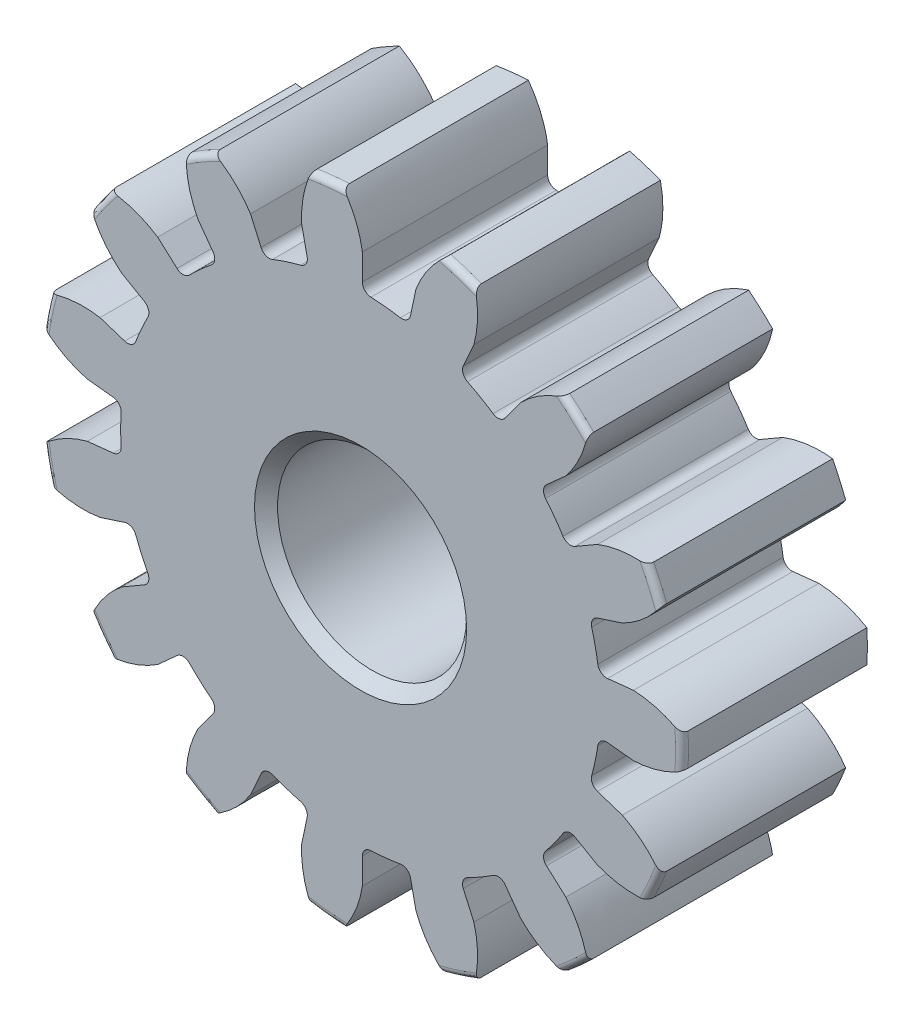
SolidWorks part; units mm, degrees
ref_plane "Front" through (0, 0, 0) normal (0, 0, 1) x (1, 0, 0)
ref_plane "Top" through (0, 0, 0) normal (0, 1, 0) x (1, 0, 0)
ref_plane "Right" through (0, 0, 0) normal (1, 0, 0) x (0, 0, -1)
sketch "Sketch1" plane through (0, 0, 0) normal (0, 0, 1) x (1, 0, 0)
  line L0 (-190.5, 0) -> (190.5, 0) construction
  circle A0 centre (0, 0) radius 10.795
  circle A1 centre (0, 0) radius 9.525 construction
  circle A3 centre (0, 0) radius 8.0556 construction
  dimension "D1" = 1.4694
  dimension "OD" = 21.59
  dimension "Ptich Dia" = 19.05
  dimension "D2" = 2.7394
  dimension "Root Dia" = 16.1112
  dimension "D3" = 1.27
  dimension "Number of Teeth" = 381
extrude "Boss-Extrude1" add sketch "Sketch1" against normal blind 9.525
sketch "Sketch2" plane through (0, 0, 0) normal (1, 0, 0) x (0, 0, -1)
  line L0 (9.525, 0) -> (19.05, 0)
  line L1 (9.525, 0) -> (9.525, 7.7391)
  line L2 (9.525, 7.7391) -> (19.05, 7.7391)
  line L3 (19.05, 7.7391) -> (19.05, 0)
  point P5 (19.05, -7.7391)
  point P6 (0, -10.795)
  point P7 (9.525, -10.795)
  point P9 (0, 10.795)
  dimension "Face Wd" = 9.525
  dimension "B Hub Dia" = 15.4781
  dimension "D O'all Lg." = 19.05
revolve "Revolve1" add sketch "Sketch2" angle 360 mid plane about L0
fillet "Fillet2" radius 0.2159 3 edges at (10.795, 0, -9.525) (10.795, 0, 0) (7.7391, 0, -9.525)
sketch "Sketch3" plane through (0, 0, 0) normal (0, 0, 1) x (1, 0, 0)
  line L0 (0, 0) -> (0, 10.795) construction
  line L1 (-2.3089, 8.9279) -> (0, 9.525)
  line L2 (-9.5921, 9.525) -> (9.5921, 9.525) construction
  line L3 (-9.2865, 7.1233) -> (9.2865, 11.9267) construction
  line L4 (-2.3089, 8.9279) -> (0, 0) construction
  line L5 (-5.7038, 7.246) -> (0, 0) construction
  line L6 (-5.7038, 7.246) -> (-0.8315, 11.0813) construction
  line L7 (-1.61, 9.08) -> (0, 0) construction
  line L8 (-1.61, 9.08) -> (0.0338, 9.3714) construction
  arc A0 (-2.3089, 8.9279) -> (-5.7038, 7.246) centre (0, 0) ccw
  circle A1 centre (0, 0) radius 9.525 construction
  circle A2 centre (0, 0) radius 9.2216 construction
  arc A3 (-2.3089, 8.9279) -> (-1.61, 9.08) centre (0, 0) cw
  circle A4 centre (0, 0) radius 10.795 construction
  point P6 (0, 9.525)
  dimension "D1" = 2.3849
  dimension "Pressure Angle" = 14.5
  dimension "D2" = 3.8158
  dimension "D3" = 6.2007
  dimension "D4" = 0.7155
  dimension "D5" = 1.6694
sketch "Sketch4" plane through (0, 0, 0) normal (0, 0, 1) x (1, 0, 0)
  line L0 (0, 0) -> (0.9902, 9.4209) construction
  line L1 (0.0599, 9.2214) -> (0.0599, 8.0554)
  line L2 (0, 9.525) -> (1.9804, 9.3169) construction
  line L3 (1.8586, 9.0324) -> (1.6162, 7.8918)
  line L4 (0.0599, 8.0554) -> (0, 0) construction
  line L5 (0, 0) -> (0, 10.795) construction
  line L6 (-5.7038, 7.246) -> (-0.8315, 11.0813) construction
  line L7 (-5.7038, 7.246) -> (-0.8315, 11.0813) construction
  arc A0 (1.6162, 7.8918) -> (0.0599, 8.0554) centre (0, 0) ccw
  arc A1 (0, 9.525) -> (1.9804, 9.3169) centre (0, 0) cw construction
  circle A2 centre (0, 0) radius 9.525 construction
  circle A3 centre (0, 0) radius 9.2216 construction
  circle A4 centre (0, 0) radius 8.0556 construction
  arc A5 (3.1173, 10.6663) -> (-0.8315, 11.0813) centre (0, 0) ccw
  spline S0 degree 2 poles (-0.8315, 11.0813) (-0.0963, 10.2474) (0.0599, 9.2214) knots 0 0 0 1 1 1
  spline S1 degree 2 poles (3.1173, 10.6663) (2.2248, 10.0035) (1.8586, 9.0324) knots 0 0 0 1 1 1
  dimension "D1" = 1.9949
extrude "Cut-Extrude1" cut sketch "Sketch4" against normal through all
fillet "Fillet1" radius 0.2992 2 edges at (1.6162, 7.8918, -4.7625) (0.0599, 8.0554, -4.7625)
pattern_circular "CirPattern1" count 15 over 360 about axis through (0, 0, -9.525) along (0, 0, 1) of "Cut-Extrude1", "Fillet1"
sketch "Sketch5" plane through (0, 0, 0) normal (0, 0, 1) x (1, 0, 0)
  circle A0 centre (0, 0) radius 3.175
  circle A1 centre (0, 0) radius 3.175 construction
  dimension "Bore Min" = 6.35
  dimension "Bore Max" = 6.35
extrude "Cut-Extrude2" cut sketch "Sketch5" against normal through all
chamfer "Chamfer1" distance 0.387 angle 45 3 edges at (7.7391, 0, -19.05) (3.175, 0, 0) (3.175, 0, -19.05)
sketch "Pitch Dia" plane through (0, 0, 0) normal (0, 0, 1) x (1, 0, 0)
  circle A0 centre (0, 0) radius 9.525 construction
  circle A1 centre (0, 0) radius 9.525
sketch "Sketch6" plane through (0, 0, -19.05) normal (0, 0, -1) x (-1, 0, 0)
  circle A1 centre (0, 0) radius 12.7
  dimension "D1" = 25.4
extrude "Cut-Extrude3" cut sketch "Sketch6" against normal blind 12.827
equation "\"D1@Boss-Extrude1\" = \"Face Wd@Sketch2\""
equation "\"D2@Sketch3\" = \"D1@Sketch3\"*1.6"
equation "\"D3@Sketch3\" = \"D1@Sketch3\"+\"D2@Sketch3\""
equation "\"D4@Sketch3\" = \"D1@Sketch3\"*.3"
equation "\"D5@Sketch3\" = \"D1@Sketch3\"-\"D4@Sketch3\""
equation "\"D1@Sketch4\" = 1.5708/(\"Number of Teeth@Sketch1\"/\"Ptich Dia@Sketch1\")"
equation "\"D1@Chamfer1\" = \"B Hub Dia@Sketch2\"*.025"
equation "\"D1@CirPattern1\" = \"Number of Teeth@Sketch1\""
equation "\"D1@Fillet1\" = \"D1@Sketch4\"*.15"
equation "\"D1@Fillet2\" = \"OD@Sketch1\"*.01"
equation "\"D1@Sketch1\" = 1.157/(\"Number of Teeth@Sketch1\"/\"Ptich Dia@Sketch1\")"
